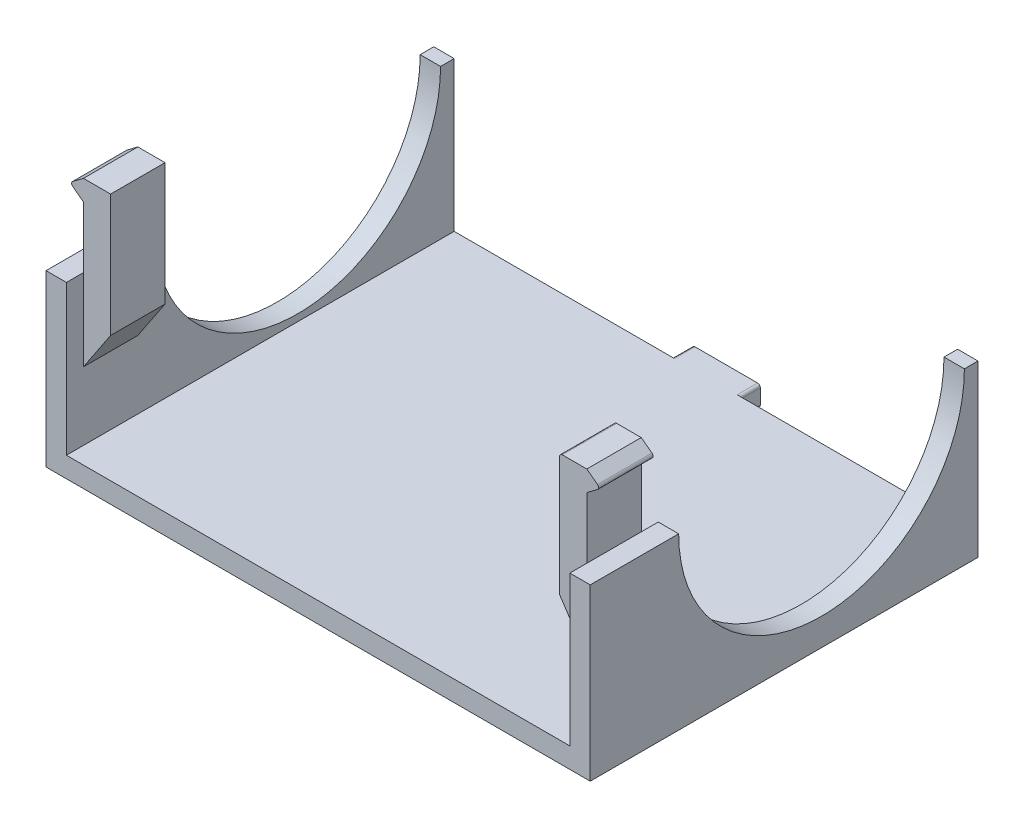
SolidWorks part; units mm, degrees
ref_plane "前视基准面" through (0, 0, 0) normal (0, 0, 1) x (1, 0, 0)
ref_plane "上视基准面" through (0, 0, 0) normal (0, 1, 0) x (1, 0, 0)
ref_plane "右视基准面" through (0, 0, 0) normal (1, 0, 0) x (0, 0, -1)
sketch "草图1" plane through (0, 0, 0) normal (0, 0, 1) x (1, 0, 0)
  line L0 (0, 0) -> (40, 0)
  line L1 (40, 0) -> (40, 12.5)
  line L2 (0, 0) -> (0, 12.5)
  line L3 (1.5, 1.5) -> (1.5, 12.5)
  line L4 (1.5, 1.5) -> (38.5, 1.5)
  line L5 (38.5, 1.5) -> (38.5, 12.5)
  line L6 (0, 12.5) -> (1.5, 12.5)
  line L7 (38.5, 12.5) -> (40, 12.5)
  dimension "D1" = 40
  dimension "D2" = 12.5
  dimension "D3" = 12.5
  dimension "D4" = 1.5
extrude "凸台-拉伸1" add sketch "草图1" along normal blind 28.5
sketch "草图2" plane through (40, 0, 0) normal (1, 0, 0) x (0, 0, -1)
  line L0 (-28.5, 12.5) -> (0, 12.5) construction
  line L1 (0, 0) -> (0, 12.5) construction
  circle A0 centre (-11.5, 12.5) radius 10.5
  dimension "D1" = 21
  dimension "D2" = 11.5
extrude "切除-拉伸1" cut sketch "草图2" against normal blind 87
ref_plane "基准面1" through (39.25, 0, 0) normal (1, 0, 0) x (0, 0, -1)
ref_plane "基准面2" through (0, 0, 12) normal (0, 0, 1) x (1, 0, 0)
ref_plane "基准面3" through (20, 0, 0) normal (1, 0, 0) x (0, 0, -1)
sketch "草图3" plane through (0, 0, 0) normal (0, 0, -1) x (-1, 0, 0)
  line L0 (-20, 1.5) -> (-20, 0) construction
  line L1 (-38.5, 1.5) -> (-1.5, 1.5) construction
  line L2 (0, 0) -> (-40, 0) construction
  line L4 (-22.5, 0) -> (-17.5, 0)
  line L5 (-22.5, 0) -> (-22.5, 1.5)
  line L6 (-22.5, 1.5) -> (-17.5, 1.5)
  line L7 (-17.5, 0) -> (-17.5, 1.5)
  line L8 (-22.5, 0) -> (-17.5, 1.5) construction
  line L9 (-22.5, 1.5) -> (-17.5, 0) construction
  point P6 (-20, 0.75)
  dimension "D1" = 5
extrude "凸台-拉伸2" add sketch "草图3" along normal blind 1.5
fillet "圆角1" radius 0.2 4 edges at (22.5, 1.5, -0.75) (22.5, 0, -0.75) (17.5, 1.5, -0.75) (17.5, 0, -0.75)
sketch "草图4" plane through (0, 12.5, 0) normal (0, 1, 0) x (1, 0, 0)
  line L0 (38.5, -22) -> (38.5, -28.5) construction
  line L1 (40, -28.5) -> (40, -22) construction
  line L2 (36.5, -27.25) -> (38.5, -27.25)
  line L3 (36.5, -27.25) -> (36.5, -23.25)
  line L4 (36.5, -23.25) -> (38.5, -23.25)
  line L5 (38.5, -27.25) -> (38.5, -23.25)
  line L6 (36.5, -27.25) -> (38.5, -23.25) construction
  line L7 (36.5, -23.25) -> (38.5, -27.25) construction
  point P4 (37.5, -25.25)
  point P11 (40, -25.25)
  dimension "D1" = 2
  dimension "D2" = 4
  dimension "D3" = 0
extrude "凸台-拉伸3" add sketch "草图4" along normal blind 6 and the other way blind 3
sketch "草图5" plane through (0, 0, 27.25) normal (0, 0, 1) x (1, 0, 0)
  line L0 (36.5, 9.5) -> (38.5, 6.5)
  line L1 (38.5, 12.5) -> (38.5, 1.5) construction
  line L2 (38.5, 6.5) -> (38.5, 9.5)
  line L3 (38.5, 9.5) -> (36.5, 9.5)
  line L4 (38.5, 18.5) -> (39.5, 17.75)
  line L5 (39.5, 17.75) -> (38.5, 17)
  line L6 (38.5, 12.5) -> (38.5, 18.5) construction
  line L7 (38.5, 17) -> (38.5, 18.5)
  point P10 (38.5, 17.75)
  dimension "D1" = 3
  dimension "D2" = 1.5
  dimension "D3" = 1
  dimension "D4" = 0
extrude "凸台-拉伸4" add sketch "草图5" against normal blind 4
fillet "圆角2" radius 0.2 1 edges at (39.5, 17.75, 25.25)
mirror "镜向1" about plane through (20, 0, 0) normal (1, 0, 0) of "凸台-拉伸2", "圆角1", "圆角2", "凸台-拉伸4", "凸台-拉伸3"
fillet "圆角3" radius 0.2 1 edges at (36.5, 18.5, 25.25)
